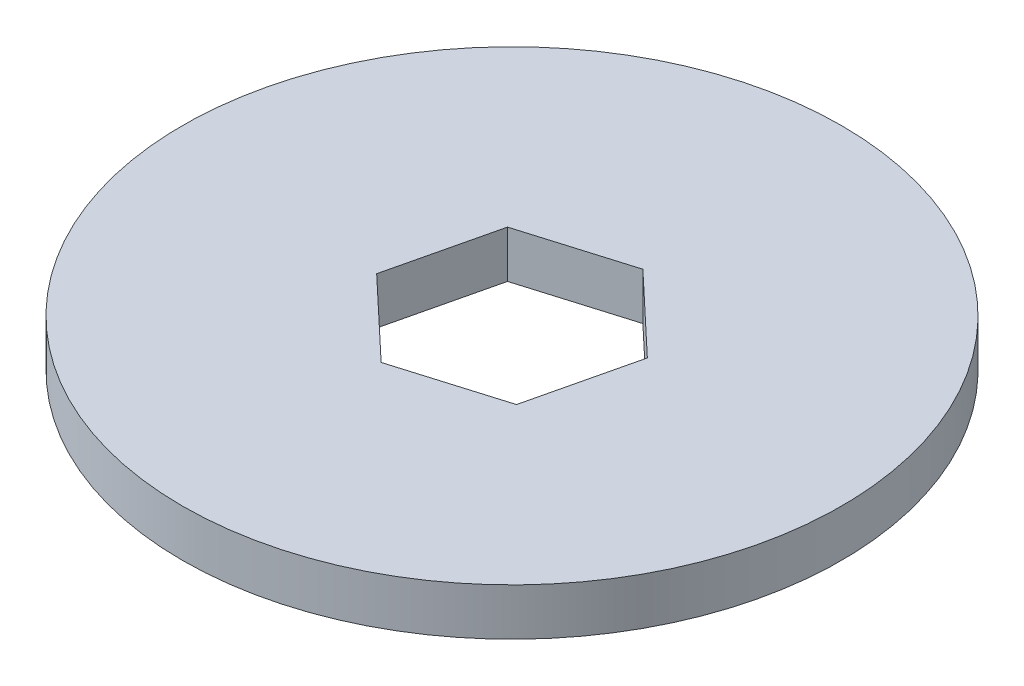
SolidWorks part; units mm, degrees
ref_plane "Front Plane" through (0, 0, 0) normal (0, 0, 1) x (1, 0, 0)
ref_plane "Top Plane" through (0, 0, 0) normal (0, 1, 0) x (1, 0, 0)
ref_plane "Right Plane" through (0, 0, 0) normal (1, 0, 0) x (0, 0, -1)
sketch "Sketch1" plane through (0, 0, 0) normal (0, 1, 0) x (1, 0, 0)
  line L7 (1.6907, 7.1348) -> (-5.3336, 5.0315)
  line L8 (-5.3336, 5.0315) -> (-7.0242, -2.1032)
  line L9 (-7.0242, -2.1032) -> (-1.6907, -7.1348)
  line L10 (-1.6907, -7.1348) -> (5.3336, -5.0315)
  line L11 (5.3336, -5.0315) -> (7.0242, 2.1032)
  line L12 (7.0242, 2.1032) -> (1.6907, 7.1348)
  circle A0 centre (0, 0) radius 22.225
  circle A1 centre (0, 0) radius 6.35 construction
  dimension "D1" = 44.45
  dimension "D2" = 12.7
extrude "Boss-Extrude1" add sketch "Sketch1" along normal blind 3.175
